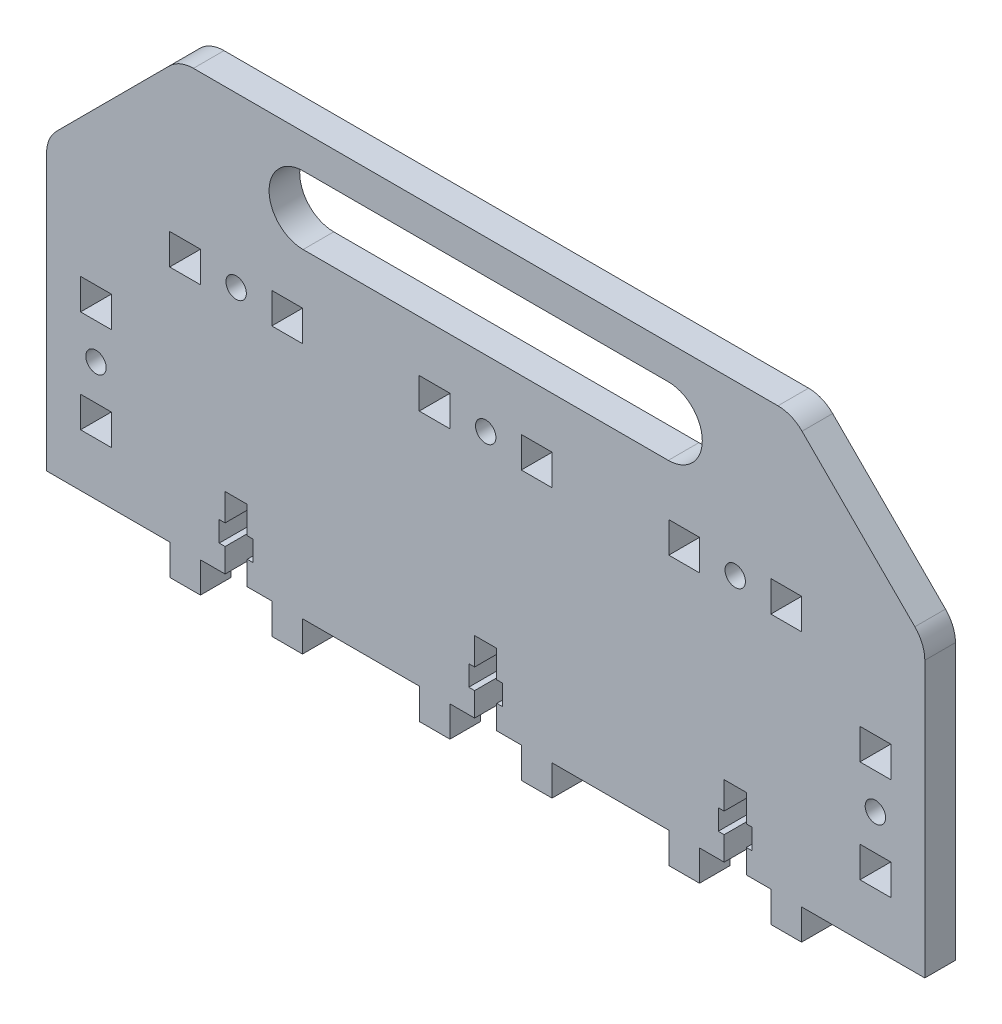
SolidWorks part; units mm, degrees
ref_plane "Front Plane" through (0, 0, 0) normal (0, 0, 1) x (1, 0, 0)
ref_plane "Top Plane" through (0, 0, 0) normal (0, 1, 0) x (1, 0, 0)
ref_plane "Right Plane" through (0, 0, 0) normal (1, 0, 0) x (0, 0, -1)
sketch "Sketch1" plane through (0, 0, 0) normal (0, 0, 1) x (1, 0, 0)
  line L0 (0, 35) -> (0, 0) construction
  line L1 (-110, 0) -> (110, 0)
  line L3 (-110, 70) -> (110, 70) construction
  line L5 (-110, 0) -> (110, 70) construction
  line L6 (-110, 70) -> (110, 0) construction
  line L7 (-53.6553, 104.05) -> (53.6553, 104.05) construction
  line L8 (-53.6553, 114.05) -> (53.6553, 114.05)
  line L9 (-53.6553, 94.05) -> (53.6553, 94.05)
  line L11 (-126.1245, 87.9283) -> (-92.9678, 121.1176)
  line L12 (-85.8933, 124.05) -> (85.8933, 124.05)
  line L13 (92.9678, 121.1176) -> (115.5775, 98.4858)
  line L15 (0, 35) -> (110, 35) construction
  line L16 (110, 0) -> (129.05, 0)
  line L17 (129.05, 0) -> (129.05, 80.8607)
  line L18 (126.1245, 87.9283) -> (115.5775, 98.4858)
  line L19 (-110, 0) -> (-129.05, 0)
  line L20 (-129.05, 0) -> (-129.05, 80.8607)
  line L22 (-110, 70) -> (-110, 0) construction
  line L23 (110, 70) -> (110, 0) construction
  arc A0 (-53.6553, 114.05) -> (-53.6553, 94.05) centre (-53.6553, 104.05) ccw
  arc A1 (53.6553, 94.05) -> (53.6553, 114.05) centre (53.6553, 104.05) ccw
  arc A4 (-126.1245, 87.9283) -> (-129.05, 80.8607) centre (-119.05, 80.8607) ccw
  arc A5 (129.05, 80.8607) -> (126.1245, 87.9283) centre (119.05, 80.8607) ccw
  arc A6 (92.9678, 121.1176) -> (85.8933, 124.05) centre (85.8933, 114.05) ccw
  arc A7 (-85.8933, 124.05) -> (-92.9678, 121.1176) centre (-85.8933, 114.05) ccw
  point P0 (0, 35)
  point P10 (0, 104.05)
  point P15 (0, 0)
  point P17 (0, 0)
  point P20 (0, 0)
  point P22 (-90.0383, 124.05)
  point P24 (94.5386, 124.05)
  point P26 (0, 0)
  point P28 (0, 0)
  point P29 (0, 0)
  point P32 (-129.05, 85)
  point P37 (-107.5694, 79.7001)
  point P38 (90.0383, 124.05)
  point P41 (-90.0383, 124.05)
  line B0 (-19.5, 0) -> (-19.5, -9)
  line B1 (-19.5, -9) -> (-10.5, -9)
  line B2 (-10.5, -9) -> (-10.5, 0)
  line B3 (-10.5, 0) -> (-3.25, 0)
  line B4 (-3.25, 0) -> (-3.25, 7)
  line B5 (-3.25, 7) -> (-4.975, 7)
  line B6 (-4.975, 7) -> (-4.975, 13)
  line B7 (-4.975, 13) -> (-3.25, 13)
  line B8 (-3.25, 13) -> (-3.25, 21)
  line B9 (-3.25, 21) -> (3.25, 21)
  line B10 (0, 21) -> (0, 0) construction
  line B11 (3.25, 13) -> (3.25, 21)
  line B12 (4.975, 13) -> (3.25, 13)
  line B13 (4.975, 7) -> (4.975, 13)
  line B14 (3.25, 7) -> (4.975, 7)
  line B15 (3.25, 0) -> (3.25, 7)
  line B16 (10.5, 0) -> (3.25, 0)
  line B17 (10.5, -9) -> (10.5, 0)
  line B18 (19.5, -9) -> (10.5, -9)
  line B19 (19.5, 0) -> (19.5, -9)
  line B20 (-92.8333, 0) -> (-92.8333, -9)
  line B21 (-92.8333, -9) -> (-83.8333, -9)
  line B22 (-83.8333, -9) -> (-83.8333, 0)
  line B23 (-83.8333, 0) -> (-76.5833, 0)
  line B24 (-76.5833, 0) -> (-76.5833, 7)
  line B25 (-76.5833, 7) -> (-78.3083, 7)
  line B26 (-78.3083, 7) -> (-78.3083, 13)
  line B27 (-78.3083, 13) -> (-76.5833, 13)
  line B28 (-76.5833, 13) -> (-76.5833, 21)
  line B29 (-76.5833, 21) -> (-70.0833, 21)
  line B30 (-73.3333, 21) -> (-73.3333, 0) construction
  line B31 (-70.0833, 13) -> (-70.0833, 21)
  line B32 (-68.3583, 13) -> (-70.0833, 13)
  line B33 (-68.3583, 7) -> (-68.3583, 13)
  line B34 (-70.0833, 7) -> (-68.3583, 7)
  line B35 (-70.0833, 0) -> (-70.0833, 7)
  line B36 (-62.8333, 0) -> (-70.0833, 0)
  line B37 (-62.8333, -9) -> (-62.8333, 0)
  line B38 (-53.8333, -9) -> (-62.8333, -9)
  line B39 (-53.8333, 0) -> (-53.8333, -9)
  line B40 (53.8333, 0) -> (53.8333, -9)
  line B41 (53.8333, -9) -> (62.8333, -9)
  line B42 (62.8333, -9) -> (62.8333, 0)
  line B43 (62.8333, 0) -> (70.0833, 0)
  line B44 (70.0833, 0) -> (70.0833, 7)
  line B45 (70.0833, 7) -> (68.3583, 7)
  line B46 (68.3583, 7) -> (68.3583, 13)
  line B47 (68.3583, 13) -> (70.0833, 13)
  line B48 (70.0833, 13) -> (70.0833, 21)
  line B49 (70.0833, 21) -> (76.5833, 21)
  line B50 (73.3333, 21) -> (73.3333, 0) construction
  line B51 (76.5833, 13) -> (76.5833, 21)
  line B52 (78.3083, 13) -> (76.5833, 13)
  line B53 (78.3083, 7) -> (78.3083, 13)
  line B54 (76.5833, 7) -> (78.3083, 7)
  line B55 (76.5833, 0) -> (76.5833, 7)
  line B56 (83.8333, 0) -> (76.5833, 0)
  line B57 (83.8333, -9) -> (83.8333, 0)
  line B58 (92.8333, -9) -> (83.8333, -9)
  line B59 (92.8333, 0) -> (92.8333, -9)
  line B60 (-73.3333, 74.525) -> (-88.3333, 74.525) construction
  line B61 (-73.3333, 79.9951) -> (-73.3333, 69.5131) construction
  line B62 (-53.8083, 79.05) -> (-62.8583, 79.05)
  line B63 (-92.8583, 70) -> (-83.8083, 70)
  line B64 (-92.8583, 70) -> (-92.8583, 79.05)
  line B65 (-92.8583, 79.05) -> (-83.8083, 79.05)
  line B66 (-83.8083, 70) -> (-83.8083, 79.05)
  line B67 (-92.8583, 70) -> (-83.8083, 79.05) construction
  line B68 (-92.8583, 79.05) -> (-83.8083, 70) construction
  line B69 (-62.8583, 70) -> (-62.8583, 79.05)
  line B70 (-53.8083, 70) -> (-62.8583, 70)
  line B71 (-53.8083, 70) -> (-53.8083, 79.05)
  circle B72 centre (-73.3333, 74.525) radius 3
  line B73 (-114.525, 35) -> (-114.525, 20) construction
  line B74 (-119.9951, 35) -> (-109.5131, 35) construction
  line B75 (-119.05, 54.525) -> (-119.05, 45.475)
  line B76 (-110, 15.475) -> (-110, 24.525)
  line B77 (-110, 15.475) -> (-119.05, 15.475)
  line B78 (-119.05, 15.475) -> (-119.05, 24.525)
  line B79 (-110, 24.525) -> (-119.05, 24.525)
  line B80 (-110, 15.475) -> (-119.05, 24.525) construction
  line B81 (-119.05, 15.475) -> (-110, 24.525) construction
  line B82 (-110, 45.475) -> (-119.05, 45.475)
  line B83 (-110, 54.525) -> (-110, 45.475)
  line B84 (-110, 54.525) -> (-119.05, 54.525)
  circle B85 centre (-114.525, 35) radius 3
  line B86 (114.525, 35) -> (114.525, 20) construction
  line B87 (119.9951, 35) -> (109.5131, 35) construction
  line B88 (119.05, 54.525) -> (119.05, 45.475)
  line B89 (110, 15.475) -> (110, 24.525)
  line B90 (110, 15.475) -> (119.05, 15.475)
  line B91 (119.05, 15.475) -> (119.05, 24.525)
  line B92 (110, 24.525) -> (119.05, 24.525)
  line B93 (110, 15.475) -> (119.05, 24.525) construction
  line B94 (119.05, 15.475) -> (110, 24.525) construction
  line B95 (110, 45.475) -> (119.05, 45.475)
  line B96 (110, 54.525) -> (110, 45.475)
  line B97 (110, 54.525) -> (119.05, 54.525)
  circle B98 centre (114.525, 35) radius 3
  line B99 (0, 74.525) -> (-15, 74.525) construction
  line B100 (0, 79.9951) -> (0, 69.5131) construction
  line B101 (19.525, 79.05) -> (10.475, 79.05)
  line B102 (-19.525, 70) -> (-10.475, 70)
  line B103 (-19.525, 70) -> (-19.525, 79.05)
  line B104 (-19.525, 79.05) -> (-10.475, 79.05)
  line B105 (-10.475, 70) -> (-10.475, 79.05)
  line B106 (-19.525, 70) -> (-10.475, 79.05) construction
  line B107 (-19.525, 79.05) -> (-10.475, 70) construction
  line B108 (10.475, 70) -> (10.475, 79.05)
  line B109 (19.525, 70) -> (10.475, 70)
  line B110 (19.525, 70) -> (19.525, 79.05)
  circle B111 centre (0, 74.525) radius 3
  line B112 (73.3333, 74.525) -> (58.3333, 74.525) construction
  line B113 (73.3333, 79.9951) -> (73.3333, 69.5131) construction
  line B114 (92.8583, 79.05) -> (83.8083, 79.05)
  line B115 (53.8083, 70) -> (62.8583, 70)
  line B116 (53.8083, 70) -> (53.8083, 79.05)
  line B117 (53.8083, 79.05) -> (62.8583, 79.05)
  line B118 (62.8583, 70) -> (62.8583, 79.05)
  line B119 (53.8083, 70) -> (62.8583, 79.05) construction
  line B120 (53.8083, 79.05) -> (62.8583, 70) construction
  line B121 (83.8083, 70) -> (83.8083, 79.05)
  line B122 (92.8583, 70) -> (83.8083, 70)
  line B123 (92.8583, 70) -> (92.8583, 79.05)
  circle B124 centre (73.3333, 74.525) radius 3
sketch_block_instance "Plot_9mm_M6_bois-1"
sketch_block "Plot_9mm_M6_bois" parameters "D1"=9, "D2"=9, "D3"=16, "D4"=30, "D5"=9.95, "D6"=6.5, "D7"=6, "D8"=8
sketch_block_instance "Plot_9mm_M6_bois-2"
sketch_block_instance "Plot_9mm_M6_bois-3"
sketch_block_instance "Insert_9mm_M6_bois-1"
sketch_block "Insert_9mm_M6_bois" parameters "D4"=6, "D1"=9.05, "D2"=9.05, "D3"=15
sketch_block_instance "Insert_9mm_M6_bois-2"
sketch_block_instance "Insert_9mm_M6_bois-5"
sketch_block_instance "Insert_9mm_M6_bois-6"
sketch_block_instance "Insert_9mm_M6_bois-7" parameters "D6"=10, "D8"=10, "D10"=10, "D1"=58.0548, "D2"=145.7413, "D3"=128.3751, "D4"=108.4636, "D5"=108.4636, "D7"=4.1109, "D9"=55.9526
extrude "Boss-Extrude3" add sketch "Sketch1" along normal blind 9
